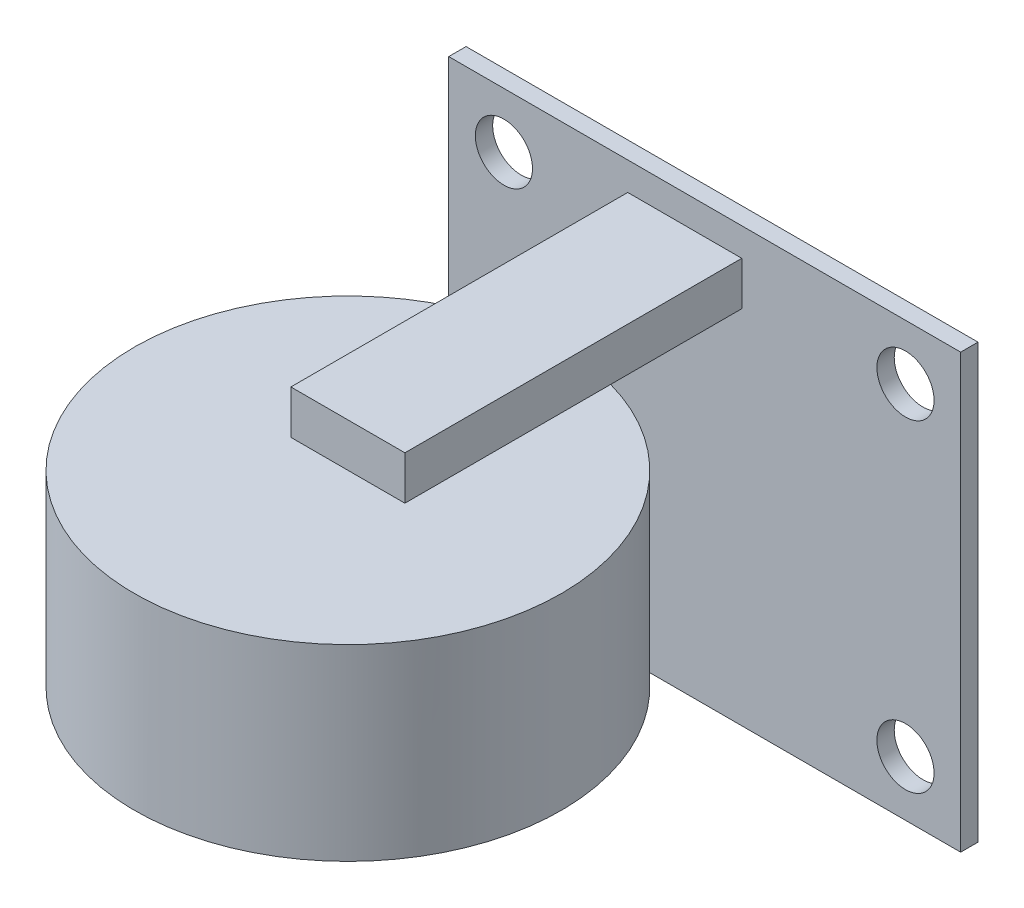
SolidWorks part; units mm, degrees
ref_plane "Front Plane" through (0, 0, 0) normal (0, 0, 1) x (1, 0, 0)
ref_plane "Top Plane" through (0, 0, 0) normal (0, 1, 0) x (1, 0, 0)
ref_plane "Right Plane" through (0, 0, 0) normal (1, 0, 0) x (0, 0, -1)
sketch "Sketch2" plane through (0, 0, 0) normal (0, 0, 1) x (1, 0, 0)
  line L0 (0, 33.2232) -> (4.8514, 33.2232) construction
  line L1 (0, 0) -> (45.0088, 0)
  line L2 (0, 0) -> (0, 38.0746)
  line L3 (0, 38.0746) -> (45.0088, 38.0746)
  line L4 (45.0088, 0) -> (45.0088, 38.0746)
  line L5 (4.8514, 33.2232) -> (4.8514, 38.0746) construction
  line L6 (0, 4.8514) -> (4.8514, 4.8514) construction
  line L7 (4.8514, 4.8514) -> (4.8514, 0) construction
  line L8 (45.0088, 33.2232) -> (40.1574, 33.2232) construction
  line L9 (40.1574, 33.2232) -> (40.1574, 38.0746) construction
  line L10 (40.1574, 0) -> (40.1574, 4.8514) construction
  circle A0 centre (4.8514, 33.2232) radius 2.5146
  circle A1 centre (4.8514, 4.8514) radius 2.5146
  circle A2 centre (40.1574, 4.8514) radius 2.5146
  circle A3 centre (40.1574, 33.2232) radius 2.5146
  dimension "D8" = 5.0292
  dimension "D9" = 5.0292
  dimension "D10" = 5.0292
  dimension "D11" = 5.0292
  dimension "D1" = 38.0746
  dimension "D2" = 45.0088
  dimension "D3" = 4.8514
  dimension "D4" = 4.8514
  dimension "D5" = 4.8514
  dimension "D6" = 4.8514
  dimension "D7" = 4.8514
  dimension "D12" = 4.8514
extrude "Boss-Extrude1" add sketch "Sketch2" along normal blind 1.524
sketch "Sketch3" plane through (0, 0, 1.524) normal (0, 0, 1) x (1, 0, 0)
  line L1 (15.7378, 35.596) -> (25.7639, 35.596)
  line L2 (15.7378, 35.596) -> (15.7378, 31.7568)
  line L3 (15.7378, 31.7568) -> (25.7639, 31.7568)
  line L4 (25.7639, 35.596) -> (25.7639, 31.7568)
extrude "Boss-Extrude2" add sketch "Sketch3" along normal blind 29.6164
sketch "Sketch4" plane through (0, 31.7568, 0) normal (0, -1, 0) x (1, 0, 0)
  line L0 (15.7378, 31.1404) -> (25.7639, 31.1404) construction
  circle A0 centre (20.7508, 31.1404) radius 18.7706
  point P4 (0, 0)
  dimension "D1" = 37.5412
extrude "Boss-Extrude3" add sketch "Sketch4" along normal blind 16.51
